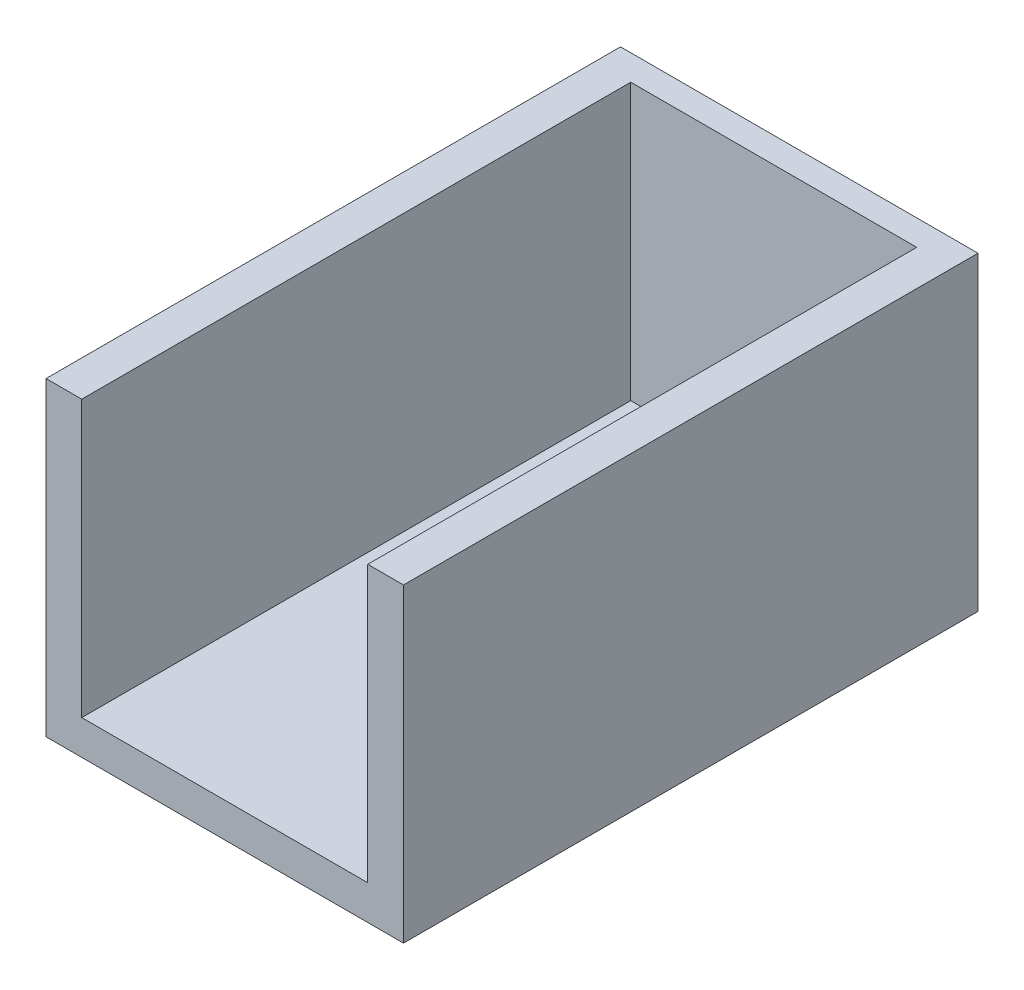
SolidWorks part; units mm, degrees
ref_plane "Front Plane" through (0, 0, 0) normal (0, 0, 1) x (1, 0, 0)
ref_plane "Top Plane" through (0, 0, 0) normal (0, 1, 0) x (1, 0, 0)
ref_plane "Right Plane" through (0, 0, 0) normal (1, 0, 0) x (0, 0, -1)
sketch "Sketch1" plane through (0, 0, 0) normal (0, 0, 1) x (1, 0, 0)
  line L1 (-14, -13.5) -> (14, -13.5)
  line L2 (-14, -13.5) -> (-14, 13.5)
  line L3 (-14, 13.5) -> (14, 13.5)
  line L4 (14, -13.5) -> (14, 13.5)
  line L5 (-14, -13.5) -> (14, 13.5) construction
  line L6 (-14, 13.5) -> (14, -13.5) construction
  line L11 (10054.9656, 9695.8597) -> (37.1131, 35.7877) construction
  line L12 (-23.2087, 23.2087) -> (23.2087, -23.2087) construction
  point P0 (0, 0)
  point P6 (0, 0)
  dimension "D1" = 28
  dimension "D2" = 27
extrude "Boss-Extrude1" add sketch "Sketch1" along normal blind 45
sketch "Sketch2" plane through (0, 0, 45) normal (0, 0, 1) x (1, 0, 0)
  line L0 (-11.2, -10.8) -> (11.2, -10.8)
  line L2 (-11.2, -10.8) -> (-11.2, 10.8)
  line L3 (-11.2, 10.8) -> (11.2, 10.8)
  line L4 (11.2, -10.8) -> (11.2, 10.8)
  line L5 (-11.2, -10.8) -> (11.2, 10.8) construction
  line L6 (-11.2, 10.8) -> (11.2, -10.8) construction
  point P0 (0, 0)
  dimension "D1" = 22.4
  dimension "D2" = 21.6
extrude "Cut-Extrude1" cut sketch "Sketch2" against normal blind 43
fillet "Fillet3" radius 2 2 edges at (14, 13.5, 22.5) (-14, 13.5, 22.5)
sketch "Sketch12" plane through (0, 0, 45) normal (0, 0, 1) x (1, 0, 0)
  line L1 (-14, 11.5) -> (-14, -13.5) construction
  line L2 (-14, 10.8) -> (14, 10.8)
  line L3 (14, -13.5) -> (14, 11.5) construction
  line L4 (14, 10.8) -> (14, 14.0388)
  line L5 (14, 14.0388) -> (-14, 14.0388)
  line L6 (-14, 14.0388) -> (-14, 10.8)
extrude "Cut-Extrude9" cut sketch "Sketch12" against normal through all
equation "\"Mount Width\"= 28mm"
equation "\"Mount Inner Size\"= \"Mount Width\" * 0.80"
equation "\"D1@Sketch1\"=\"Mount Width\""
equation "\"Mount Height\"= 27mm"
equation "\"D2@Sketch1\"=\"Mount Height\""
equation "\"D1@Sketch2\"=\"Mount Width\" * 0.8"
equation "\"D2@Sketch2\"=\"Mount Height\" * 0.8"
equation "\"Hole Dim\"= 2.5mm"
